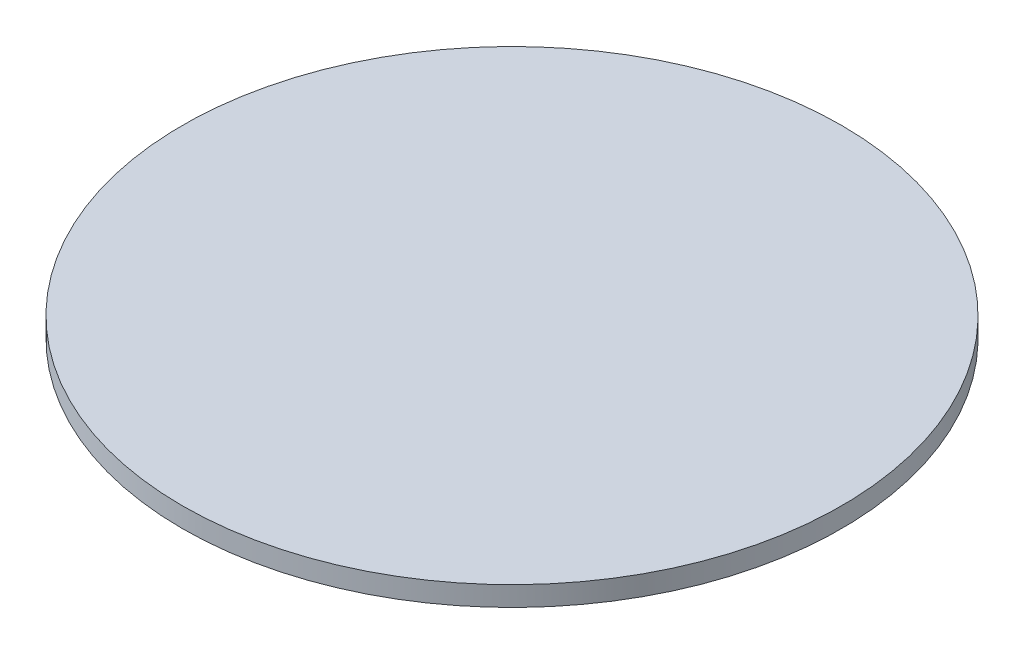
SolidWorks part; units mm, degrees
ref_plane "Front Plane" through (0, 0, 0) normal (0, 0, 1) x (1, 0, 0)
ref_plane "Top Plane" through (0, 0, 0) normal (0, 1, 0) x (1, 0, 0)
ref_plane "Right Plane" through (0, 0, 0) normal (1, 0, 0) x (0, 0, -1)
sketch "Sketch1" plane through (0, 0, 0) normal (0, 1, 0) x (1, 0, 0)
  circle A0 centre (0, 0) radius 50
  dimension "D1" = 100
extrude "Boss-Extrude1" add sketch "Sketch1" along normal blind 3
